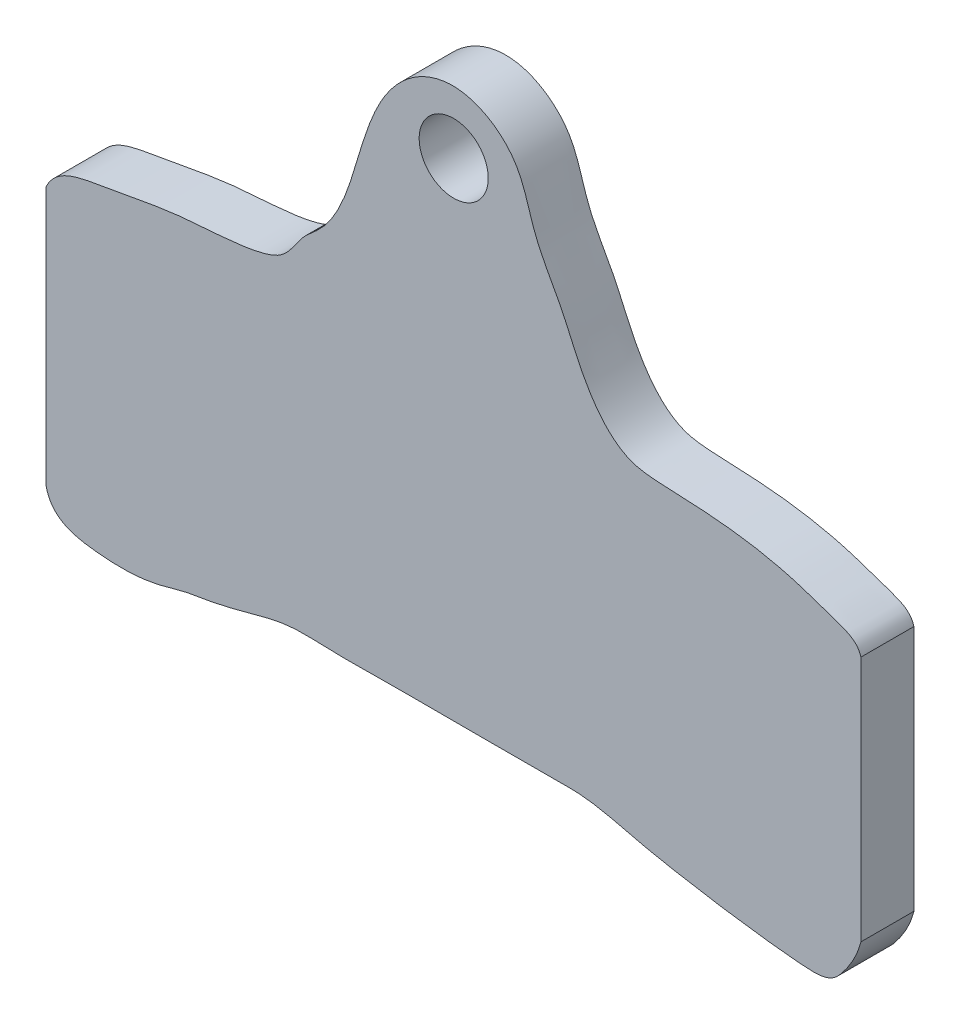
SolidWorks part; units mm, degrees
material "Plain Carbon Steel"
ref_plane "Front Plane" through (0, 0, 0) normal (0, 0, 1) x (1, 0, 0)
ref_plane "Top Plane" through (0, 0, 0) normal (0, 1, 0) x (1, 0, 0)
ref_plane "Right Plane" through (0, 0, 0) normal (1, 0, 0) x (0, 0, -1)
sketch "Sketch1" plane through (0, 0, 0) normal (0, 0, 1) x (1, 0, 0)
  line L0 (1.7443, 33.7346) -> (1.7443, 15.1875)
  line L1 (60.1059, 33.7346) -> (60.1059, 16.0713)
  circle A0 centre (30.9403, 50.0958) radius 2.4751
  spline S0 degree 3 poles (1.7443, 33.7346) (2.4213, 35.2016) (4.7953, 35.6153) (7.8978, 36.1587) (10.4501, 36.6374) (13.5716, 36.9027) (16.2645, 37.0498) (19.0425, 37.8976) (19.8704, 39.7065) (22.676, 41.8513) (24.0715, 46.8241) (25.7017, 51.8846) (28.6765, 54.2078) (31.0123, 54.8048) (33.5639, 54.0065) (35.9225, 51.7609) (36.5608, 48.153) (38.8025, 44.6774) (40.2226, 40.7434) (42.863, 37.4816) (46.5674, 37.2927) (50.5185, 37.1346) (54.39, 36.4794) (57.226, 35.4782) (58.8611, 34.9495) (59.9141, 34.4643) (60.1059, 33.7346) knots 0 0 0 0 0.05473 0.084978 0.12185 0.153315 0.204192 0.225954 0.25894 0.273959 0.359356 0.444754 0.470011 0.500151 0.532763 0.567774 0.618621 0.667419 0.723451 0.78132 0.809895 0.860501 0.933915 0.957807 0.974937 1 1 1 1
  spline S1 degree 3 poles (1.7443, 15.1875) (2.1363, 13.3639) (4.688, 12.8896) (7.7796, 12.7222) (9.8156, 13.0245) (11.621, 13.6112) (13.6011, 13.8709) (16.1691, 14.51) (18.9977, 15.346) (22.3636, 15.1266) (26.6845, 15.2185) (31.8431, 15.175) (36.0395, 15.1969) (38.5114, 15.1812) (40.8703, 15.2401) (43.6555, 14.4027) (46.8021, 13.8067) (49.8849, 13.2647) (52.9268, 12.8421) (55.8509, 12.5233) (57.8932, 12.4547) (59.2573, 14.0253) (59.8663, 15.1413) (60.1059, 16.0713) knots 0 0 0 0 0.074493 0.112517 0.153165 0.173137 0.204805 0.249876 0.302184 0.346612 0.412539 0.512862 0.59742 0.616702 0.63318 0.711962 0.755809 0.789268 0.864424 0.903513 0.936327 0.954797 1 1 1 1
extrude "Extrude1" add sketch "Sketch1" along normal blind 3.8
